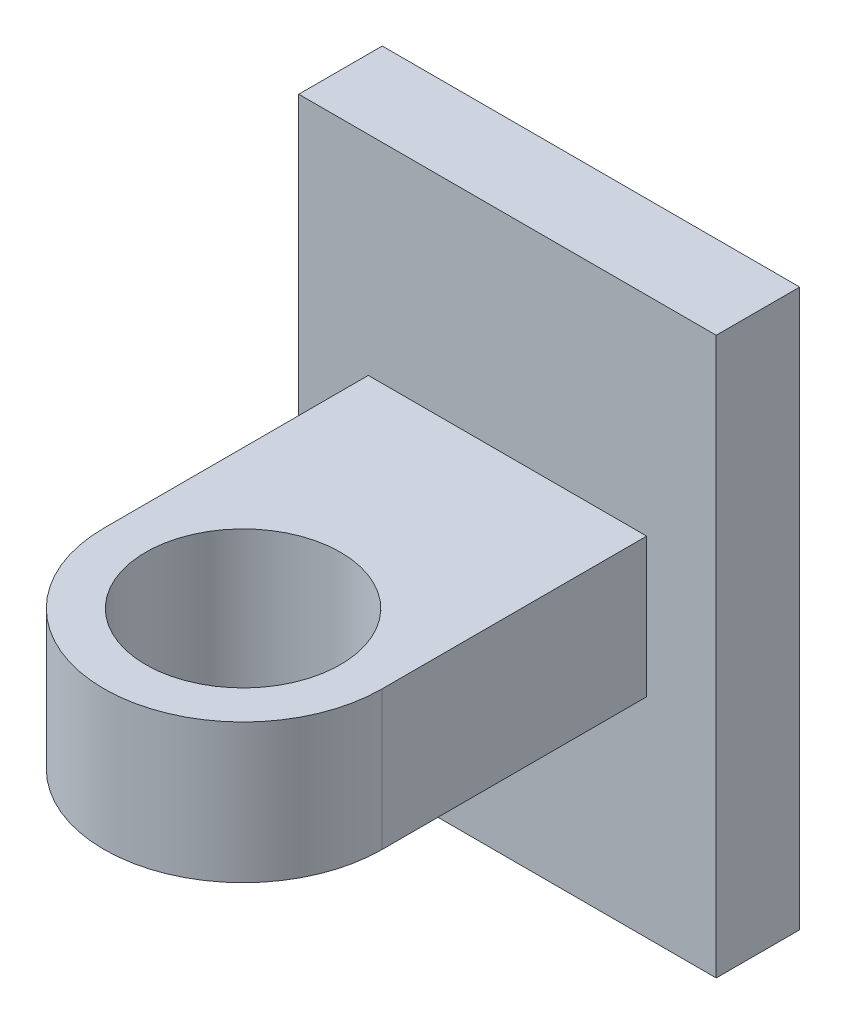
SolidWorks part; units mm, degrees
ref_plane "Ön Düzlem" through (0, 0, 0) normal (0, 0, 1) x (1, 0, 0)
ref_plane "Üst Düzlem" through (0, 0, 0) normal (0, 1, 0) x (1, 0, 0)
ref_plane "Sağ Düzlem" through (0, 0, 0) normal (1, 0, 0) x (0, 0, -1)
sketch "Sketch1" plane through (0, 0, 0) normal (0, 0, 1) x (1, 0, 0)
  line L1 (-7.5, 10) -> (7.5, 10)
  line L2 (-7.5, 10) -> (-7.5, -10)
  line L3 (-7.5, -10) -> (7.5, -10)
  line L4 (7.5, 10) -> (7.5, -10)
  line L5 (-7.5, 10) -> (7.5, -10) construction
  line L6 (-7.5, -10) -> (7.5, 10) construction
  point P0 (0, 0)
  dimension "D1" = 20
  dimension "D2" = 15
extrude "Boss-Extrude2" add sketch "Sketch1" along normal blind 3
sketch "Sketch2" plane through (0, 0, 0) normal (0, 1, 0) x (1, 0, 0)
  line L0 (-5, -3) -> (5, -3)
  line L2 (7.5, -3) -> (-7.5, -3) construction
  line L3 (5, -3) -> (5, -12.5)
  line L4 (-5, -3) -> (-5, -12.5)
  arc A0 (5, -12.5) -> (-5, -12.5) centre (0, -12.5) cw
  circle A1 centre (0, -12.5) radius 3.5
  point P4 (0, -3)
  point P9 (0, -17.5)
  dimension "D4" = 7
  dimension "D1" = 10
  dimension "D2" = 14.5
extrude "Boss-Extrude3" add sketch "Sketch2" along normal mid plane 5
